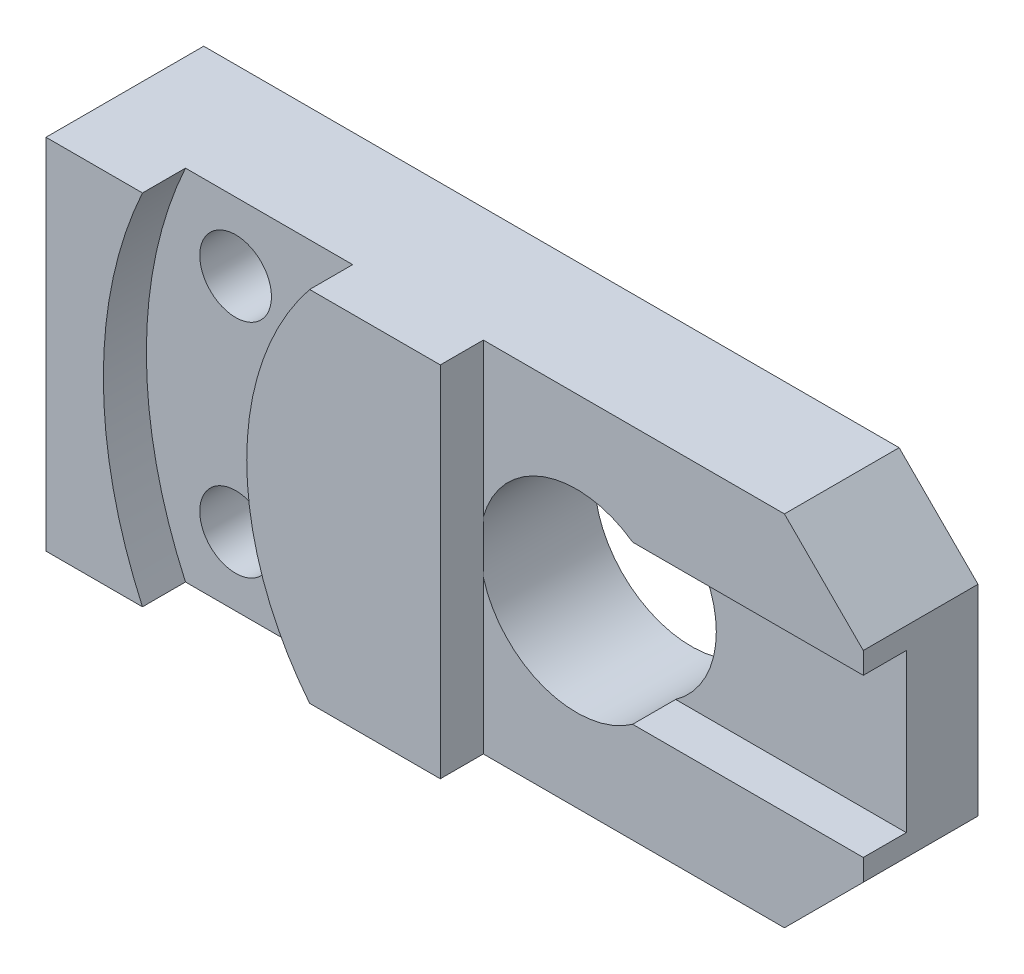
SolidWorks part; units mm, degrees
ref_plane "Front Plane" through (0, 0, 0) normal (0, 0, 1) x (1, 0, 0)
ref_plane "Top Plane" through (0, 0, 0) normal (0, 1, 0) x (1, 0, 0)
ref_plane "Right Plane" through (0, 0, 0) normal (1, 0, 0) x (0, 0, -1)
sketch "Sketch1" plane through (0, 0, 0) normal (0, 0, 1) x (1, 0, 0)
  line L1 (-54, 25) -> (54, 25)
  line L2 (-54, 25) -> (-54, -25)
  line L3 (-54, -25) -> (54, -25)
  line L4 (54, 25) -> (54, -25)
  line L5 (-54, 25) -> (54, -25) construction
  line L6 (-54, -25) -> (54, 25) construction
  point P0 (0, 0)
  dimension "D1" = 50
  dimension "D2" = 108
extrude "Boss-Extrude1" add sketch "Sketch1" along normal blind 22
sketch "Sketch2" plane through (0, 0, 22) normal (0, 0, 1) x (1, 0, 0)
  line L0 (1, 25) -> (1, -25)
  line L1 (54, 25) -> (-54, 25) construction
  line L2 (-54, -25) -> (54, -25) construction
  line L3 (54, -25) -> (54, 25) construction
  line L4 (-17.225, 25) -> (-40.5436, 25)
  line L5 (-40.5436, -25) -> (-17.225, -25)
  line L6 (14, -25) -> (14, 25)
  line L7 (14, -25) -> (14, 25) construction
  line L8 (1, 25) -> (54, 25)
  line L9 (54, 25) -> (54, -25)
  line L10 (54, -25) -> (1, -25)
  arc A0 (-17.225, 25) -> (-17.225, -25) centre (14, 0) ccw
  arc A1 (-40.5436, 25) -> (-40.5436, -25) centre (14, 0) ccw
  dimension "D3" = 120
  dimension "D4" = 80
  dimension "D1" = 53
  dimension "D2" = 40
extrude "Cut-Extrude1" cut sketch "Sketch2" against normal blind 6
sketch "Sketch3" plane through (0, 0, 16) normal (0, 0, 1) x (1, 0, 0)
  circle A0 centre (14, 0) radius 13.5
  dimension "D1" = 27
extrude "Cut-Extrude2" cut sketch "Sketch3" against normal up to next
sketch "Sketch4" plane through (0, 0, 16) normal (0, 0, 1) x (1, 0, 0)
  line L0 (54, 0) -> (14, 0) construction
  line L1 (54, 25) -> (54, -25) construction
  line L2 (54, 11) -> (14, 11)
  line L3 (54, -11) -> (14, -11)
  line L4 (54, 11) -> (54, -11)
  line L5 (14, 11) -> (14, -11)
  dimension "D1" = 11
  dimension "D2" = 11
extrude "Cut-Extrude3" cut sketch "Sketch4" against normal blind 6
chamfer "Chamfer1" distance 11 angle 45 2 edges at (54, -25, 8) (54, 25, 8)
sketch "Sketch5" plane through (0, 0, 16) normal (0, 0, 1) x (1, 0, 0)
  line L0 (14, 0) -> (-54, 0) construction
  line L1 (-54, 25) -> (-54, -25) construction
  circle A0 centre (14, 0) radius 50 construction
  circle A1 centre (-33.5531, 15.45) radius 5
  circle A2 centre (-33.5531, -15.45) radius 5
  dimension "D1" = 100
  dimension "D2" = 15.45
  dimension "D3" = 10
extrude "Cut-Extrude4" cut sketch "Sketch5" against normal up to next
